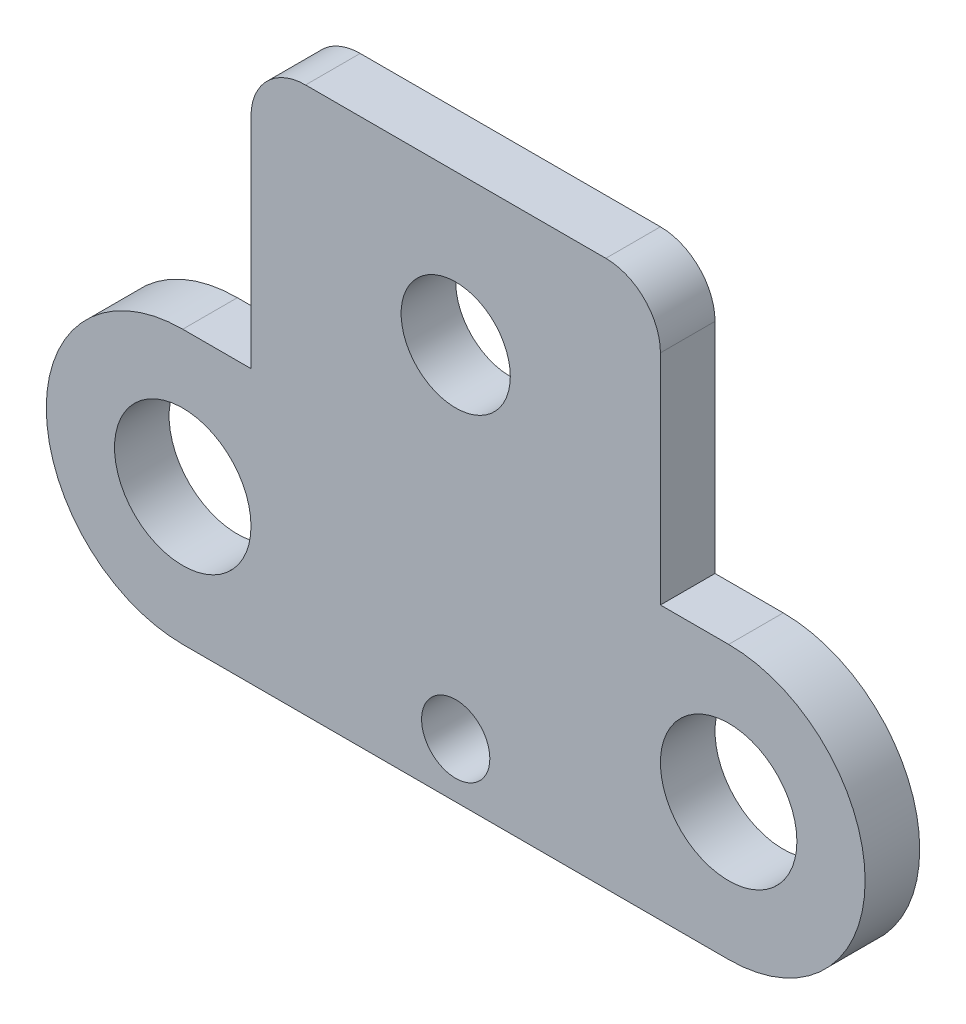
SolidWorks part; units mm, degrees
material "Alloy Steel"
ref_plane "Front Plane" through (0, 0, 0) normal (0, 0, 1) x (1, 0, 0)
ref_plane "Top Plane" through (0, 0, 0) normal (0, 1, 0) x (1, 0, 0)
ref_plane "Right Plane" through (0, 0, 0) normal (1, 0, 0) x (0, 0, -1)
other "Configuration Table"
sketch "Sketch1" plane through (0, 0, 0) normal (0, 0, 1) x (1, 0, 0)
  line L0 (0, 0) -> (20, 0) construction
  line L1 (0, 5) -> (20, 5)
  line L2 (0, -5) -> (20, -5)
  line L3 (10, 0) -> (10, 30.2937) construction
  arc A0 (0, 5) -> (0, -5) centre (0, 0) ccw
  arc A1 (20, -5) -> (20, 5) centre (20, 0) ccw
  circle A2 centre (0, 0) radius 2.5
  circle A3 centre (20, 0) radius 2.5
  circle A4 centre (10, -3) radius 1.25
  point P3 (10, 0)
  dimension "D3" = 5
  dimension "D4" = 5
  dimension "D5" = 2.5
  dimension "D1" = 20
  dimension "D2" = 10
  dimension "D6" = 3
extrude "Boss-Extrude1" add sketch "Sketch1" along normal mid plane 2
sketch "Sketch2" plane through (0, 0, 0) normal (0, 0, 1) x (1, 0, 0)
  line L0 (20, 5) -> (0, 5) construction
  line L1 (2.5, 5) -> (17.5, 5)
  line L2 (2.5, 5) -> (2.5, 15)
  line L3 (2.5, 15) -> (17.5, 15)
  line L4 (17.5, 5) -> (17.5, 15)
  line L6 (10, -3) -> (10, 17.1802) construction
  circle A0 centre (10, 9.5) radius 2
  dimension "D3" = 4
  dimension "D1" = 15
  dimension "D2" = 10
  dimension "D4" = 12.5
extrude "Boss-Extrude2" add sketch "Sketch2" along normal mid plane 2
fillet "Fillet1" radius 2 2 edges at (17.5, 15, 0) (2.5, 15, 0)
ref_plane "Plane1" through (0, 0, 4) normal (0, 0, 1) x (1, 0, 0)
sketch "Sketch3" plane through (0, 0, -1) normal (0, 0, -1) x (-1, 0, 0)
  point P0 (-10, -3)
ref_plane "Plane2" through (10, 0, 0) normal (1, 0, 0) x (0, 0, -1)
